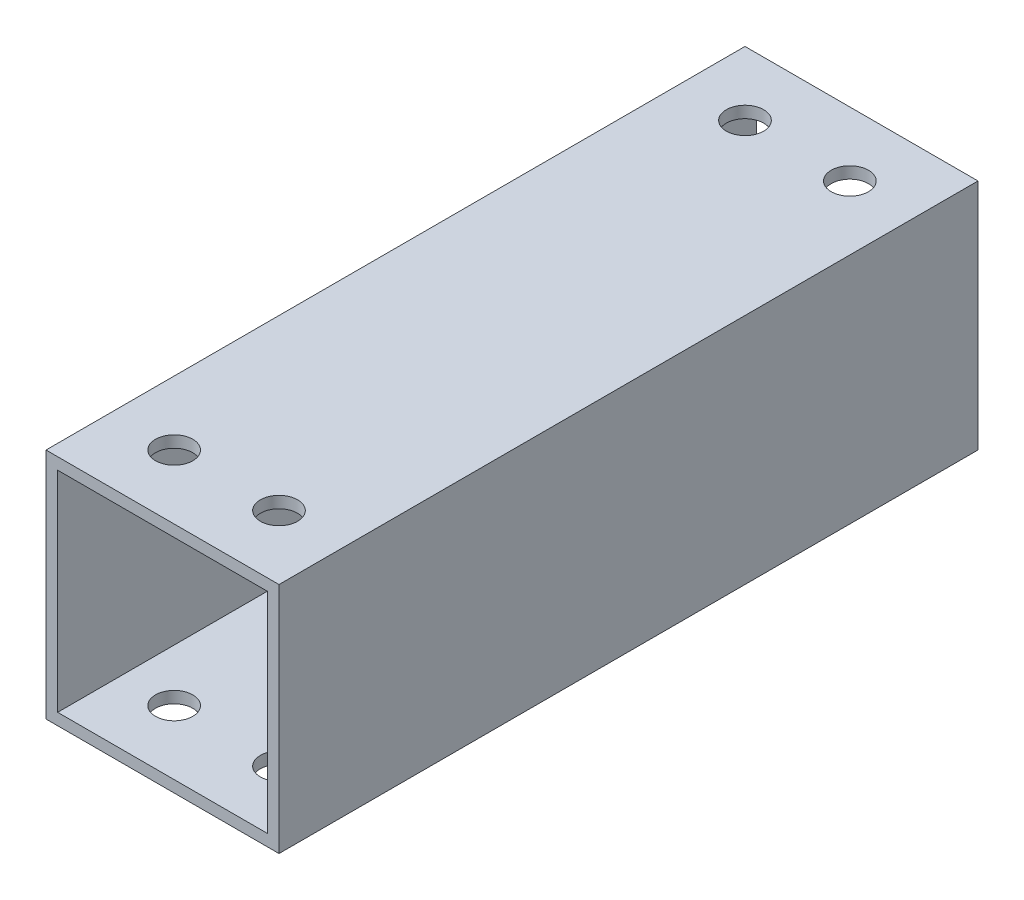
SolidWorks part; units mm, degrees
material "6061-T6 (SS)"
ref_plane "前视基准面" through (0, 0, 0) normal (0, 0, 1) x (1, 0, 0)
ref_plane "上视基准面" through (0, 0, 0) normal (0, 1, 0) x (1, 0, 0)
ref_plane "右视基准面" through (0, 0, 0) normal (1, 0, 0) x (0, 0, -1)
sketch "草图1" plane through (0, 0, 0) normal (0, 0, 1) x (1, 0, 0)
  line L1 (-10, 10) -> (10, 10)
  line L2 (-10, 10) -> (-10, -10)
  line L3 (-10, -10) -> (10, -10)
  line L4 (10, 10) -> (10, -10)
  line L5 (-10, 10) -> (10, -10) construction
  line L6 (-10, -10) -> (10, 10) construction
  line L7 (-9, 9) -> (9, 9)
  line L8 (-9, 9) -> (-9, -9)
  line L9 (-9, -9) -> (9, -9)
  line L10 (9, 9) -> (9, -9)
  line L11 (-9, 9) -> (9, -9) construction
  line L12 (-9, -9) -> (9, 9) construction
  point P0 (0, 0)
  point P6 (0, 0)
  dimension "D1" = 20
  dimension "D2" = 20
  dimension "D3" = 18
  dimension "D4" = 18
extrude "凸台-拉伸1" add sketch "草图1" along normal blind 60
sketch "草图2" plane through (0, 10, 0) normal (0, 1, 0) x (1, 0, 0)
  line L1 (-10, 0) -> (10, 0) construction
  line L2 (-10, 0) -> (-10, -60) construction
  line L3 (-10, -60) -> (10, -60) construction
  line L4 (10, 0) -> (10, -60) construction
  line L5 (-10, 0) -> (10, -60) construction
  line L6 (-10, -60) -> (10, 0) construction
  line L7 (-10, 0) -> (10, 0) construction
  line L8 (-10, 0) -> (-10, -60) construction
  line L9 (-10, -60) -> (10, -60) construction
  line L10 (10, 0) -> (10, -60) construction
  line L11 (-10, 0) -> (10, -60) construction
  line L12 (-10, -60) -> (10, 0) construction
  line L13 (-4.5, -5.5) -> (4.5, -5.5) construction
  line L14 (-4.5, -5.5) -> (-4.5, -54.5) construction
  line L15 (-4.5, -54.5) -> (4.5, -54.5) construction
  line L16 (4.5, -5.5) -> (4.5, -54.5) construction
  line L17 (0, -54.5) -> (0, -5.5) construction
  line L18 (-4.5, -30) -> (4.5, -30) construction
  circle A0 centre (-4.5, -5.5) radius 1.6
  circle A1 centre (4.5, -5.5) radius 1.6
  circle A2 centre (4.5, -54.5) radius 1.6
  circle A3 centre (-4.5, -54.5) radius 1.6
  point P4 (0, -30)
  point P7 (0, -30)
  point P10 (0, -30)
  dimension "D1" = 60
  dimension "D2" = 9
  dimension "D3" = 49
extrude "切除-拉伸1" cut sketch "草图2" against normal through all
